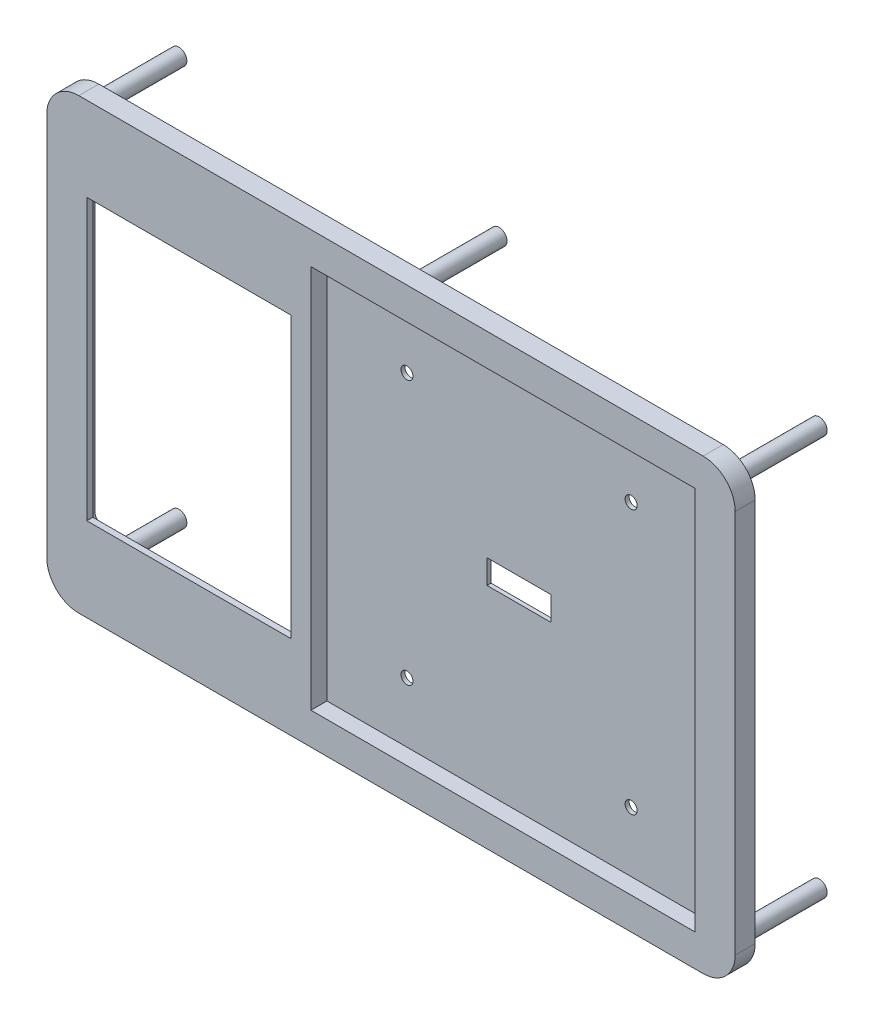
SolidWorks part; units mm, degrees
ref_plane "Спереди" through (0, 0, 0) normal (0, 0, 1) x (1, 0, 0)
ref_plane "Сверху" through (0, 0, 0) normal (0, 1, 0) x (1, 0, 0)
ref_plane "Справа" through (0, 0, 0) normal (1, 0, 0) x (0, 0, -1)
sketch "Эскиз1" plane through (0, 0, 0) normal (0, 0, 1) x (1, 0, 0)
  line L1 (0, 0) -> (172, 0)
  line L2 (0, 0) -> (0, 112)
  line L3 (0, 112) -> (172, 112)
  line L4 (172, 0) -> (172, 112)
  dimension "D1" = 172
  dimension "D2" = 112
extrude "Бобышка-Вытянуть1" add sketch "Эскиз1" along normal blind 5
fillet "Скругление2" radius 8 4 edges at (0, 0, 2.5) (172, 0, 2.5) (172, 112, 2.5) (0, 112, 2.5)
shell "Оболочка2" thickness 3
sketch "Эскиз2" plane through (0, 0, 5) normal (0, 0, 1) x (1, 0, 0)
  line L0 (8, 0) -> (164, 0) construction
  line L1 (10, 91) -> (61, 91)
  line L2 (10, 91) -> (10, 21)
  line L3 (10, 21) -> (61, 21)
  line L4 (61, 91) -> (61, 21)
  line L5 (0, 104) -> (0, 8) construction
  line L7 (164, 112) -> (8, 112) construction
  dimension "D1" = 51
  dimension "D2" = 70
  dimension "D3" = 21
  dimension "D4" = 10
  dimension "D5" = 21
extrude "Вырез-Вытянуть1" cut sketch "Эскиз2" against normal blind 5
sketch "Эскиз3" plane through (0, 0, 5) normal (0, 0, 1) x (1, 0, 0)
  line L1 (65, 105) -> (163, 105)
  line L2 (65, 105) -> (65, 7)
  line L3 (65, 7) -> (163, 7)
  line L4 (163, 105) -> (163, 7)
  line L5 (61, 21) -> (61, 91) construction
  line L6 (164, 112) -> (8, 112) construction
  dimension "D1" = 98
  dimension "D2" = 98
  dimension "D3" = 7
  dimension "D4" = 4
extrude "Бобышка-Вытянуть2" add sketch "Эскиз3" against normal blind 5
sketch "Эскиз4" plane through (0, 0, 5) normal (0, 0, 1) x (1, 0, 0)
  line L0 (61, 21) -> (61, 91) construction
  line L1 (66, 104) -> (162, 104)
  line L2 (66, 104) -> (66, 8)
  line L3 (66, 8) -> (162, 8)
  line L4 (162, 104) -> (162, 8)
  line L5 (164, 112) -> (8, 112) construction
  dimension "D1" = 96
  dimension "D2" = 96
  dimension "D3" = 5
  dimension "D4" = 8
extrude "Вырез-Вытянуть2" cut sketch "Эскиз4" against normal blind 4
sketch "Эскиз8" plane through (0, 0, 2) normal (0, 0, -1) x (-1, 0, 0)
  line L0 (0, 104) -> (0, 8) construction
  line L1 (-63, 95) -> (-7, 95)
  line L2 (-63, 95) -> (-63, 17)
  line L3 (-63, 17) -> (-7, 17)
  line L4 (-7, 95) -> (-7, 17)
  line L5 (-164, 112) -> (-8, 112) construction
  line L9 (-8, 0) -> (-164, 0) construction
  dimension "D1" = 56
  dimension "D2" = 78
  dimension "D3" = 7
  dimension "D4" = 17
  dimension "D5" = 17
extrude "Вытянуть-Тонкостенный1" add sketch "Эскиз8" along normal blind 2 separate body thin thin type one direction wall 2
sketch "Эскиз26" plane through (0, 0, 0) normal (0, 0, -1) x (-1, 0, 0)
  line L0 (0, 104) -> (0, 8) construction
  line L1 (-63, 95) -> (-7, 95)
  line L2 (-63, 95) -> (-63, 17)
  line L3 (-63, 17) -> (-7, 17)
  line L4 (-7, 95) -> (-7, 17)
  dimension "D1" = 56
  dimension "D2" = 78
  dimension "D3" = 7
extrude "Вырез-Вытянуть4" cut sketch "Эскиз26" against normal blind 3.5
fillet "Скругление3" radius 2 4 edges at (63, 95, 2.75) (63, 17, 2.75) (7, 17, 2.75) (7, 95, 2.75)
fillet "Скругление5" radius 2 4 edges at (7, 17, 1) (63, 17, 1) (7, 95, 1) (63, 95, 1)
sketch "Эскиз9" plane through (0, 0, 2) normal (0, 0, -1) x (-1, 0, 0)
  line L0 (-172, 8) -> (-172, 104) construction
  line L1 (-164, 112) -> (-8, 112) construction
  circle A0 centre (-166, 106) radius 2
  dimension "D1" = 6
  dimension "D2" = 6
extrude "Бобышка-Вытянуть3" add sketch "Эскиз9" along normal blind 24
sketch "Эскиз10" plane through (0, 0, 2) normal (0, 0, -1) x (-1, 0, 0)
  line L0 (-8, 0) -> (-164, 0) construction
  line L1 (-172, 8) -> (-172, 104) construction
  circle A0 centre (-166, 6) radius 2
  dimension "D1" = 6
  dimension "D2" = 6
extrude "Бобышка-Вытянуть4" add sketch "Эскиз10" along normal blind 24
sketch "Эскиз11" plane through (0, 0, 2) normal (0, 0, -1) x (-1, 0, 0)
  line L0 (-164, 112) -> (-8, 112) construction
  line L2 (0, 104) -> (0, 8) construction
  circle A0 centre (-6, 106) radius 2
  dimension "D1" = 6
  dimension "D2" = 6
extrude "Бобышка-Вытянуть5" add sketch "Эскиз11" along normal blind 24
sketch "Эскиз12" plane through (0, 0, 2) normal (0, 0, -1) x (-1, 0, 0)
  line L0 (-8, 0) -> (-164, 0) construction
  line L1 (0, 104) -> (0, 8) construction
  circle A0 centre (-6, 6) radius 2
  dimension "D1" = 6
  dimension "D2" = 6
extrude "Бобышка-Вытянуть6" add sketch "Эскиз12" along normal blind 24
hole_wizard "Зенковка для  винта с плоской головкой M22" positions "Эскиз16" profile "Эскиз15" countersink size "M2" standard "Ansi Metric" end condition through all
sketch "Эскиз16" plane through (0, 0, 1) normal (0, 0, 1) x (1, 0, 0)
  line L5 (162, 8) -> (162, 104) construction
  line L6 (66, 8) -> (162, 8) construction
  line L9 (66, 104) -> (66, 8) construction
  line L10 (162, 104) -> (66, 104) construction
  line L11 (162, 8) -> (162, 104) construction
  point P0 (86, 89)
  point P2 (86, 23)
  point P4 (142, 23)
  point P6 (142, 89)
  dimension "D1" = 15
  dimension "D2" = 15
  dimension "D3" = 20
  dimension "D4" = 15
  dimension "D5" = 15
  dimension "D6" = 20
  dimension "D7" = 20
  dimension "D8" = 20
sketch "Эскиз15" plane through (86, 89, 1) normal (1, 0, 0) x (0, -1, 0)
  line L0 (0, 0) -> (0, 23)
  line L1 (0, 23) -> (1.2, 23)
  line L2 (1.2, 23) -> (1.2, 1.3)
  line L3 (1.2, 1.3) -> (1.5, 1)
  line L4 (1.5, 1) -> (1.5, 0)
  line L6 (1.5, 0) -> (0, 0)
  line L7 (-1.2, 1.3) -> (-1.5, 1) construction
  line L11 (0, -6.35) -> (0, 107.95) construction
  dimension "Диаметр сквозного отверстия" = 2.4
  dimension "Глубина сквозного отверстия" = 23
  dimension "Диаметр зенковки" = 3
  dimension "Угол зенковки" = 90
  dimension "Утопленность" = 1
sketch "Эскиз20" plane through (0, 0, 1) normal (0, 0, 1) x (1, 0, 0)
  line L0 (162, 104) -> (66, 104) construction
  line L1 (106, 59) -> (122, 59)
  line L2 (106, 59) -> (106, 53)
  line L3 (106, 53) -> (122, 53)
  line L4 (122, 59) -> (122, 53)
  line L5 (66, 8) -> (162, 8) construction
  line L6 (66, 104) -> (66, 8) construction
  line L7 (162, 8) -> (162, 104) construction
  point P8 (66, 56)
  point P11 (162, 56)
  dimension "D1" = 45
  dimension "D2" = 45
  dimension "D3" = 40
  dimension "D4" = 40
extrude "Вырез-Вытянуть3" cut sketch "Эскиз20" against normal through all
sketch "Эскиз22" plane through (0, 0, 2) normal (0, 0, -1) x (-1, 0, 0)
  line L0 (-164, 112) -> (-8, 112) construction
  line L1 (-172, 8) -> (-172, 104) construction
  line L4 (-8, 0) -> (-164, 0) construction
  circle A0 centre (-86, 107) radius 2
  circle A1 centre (-86, 5) radius 2
  dimension "D1" = 5
  dimension "D3" = 5
  dimension "D2" = 86
extrude "Бобышка-Вытянуть18" add sketch "Эскиз22" along normal blind 24 separate body
hole_wizard "Диаметр отверстия Ø2.0 (2)1" positions "Эскиз14" profile "Эскиз13" hole size "Ø2.0" standard "Ansi Metric"
sketch "Эскиз14" plane through (0, 0, -22) normal (0, 0, -1) x (-1, 0, 0)
  point P0 (-6, 106)
  point P3 (-6, 6)
  point P6 (-166, 6)
  point P9 (-166, 106)
  point P12 (-86, 107)
  point P15 (-86, 5)
sketch "Эскиз13" plane through (6, 106, -22) normal (1, 0, 0) x (0, 1, 0)
  line L0 (0, 0) -> (0, 15.6009)
  line L1 (0, 15.6009) -> (1, 15)
  line L2 (1, 15) -> (1, 0)
  line L5 (1, 0) -> (0, 0)
  line L10 (0, 15.6009) -> (-1, 15) construction
  line L11 (0, -6.35) -> (0, 107.95) construction
  dimension "Диаметр отверстия" = 2
  dimension "Глубина отверстия" = 15
  dimension "Угол заточки сверла" = 118
